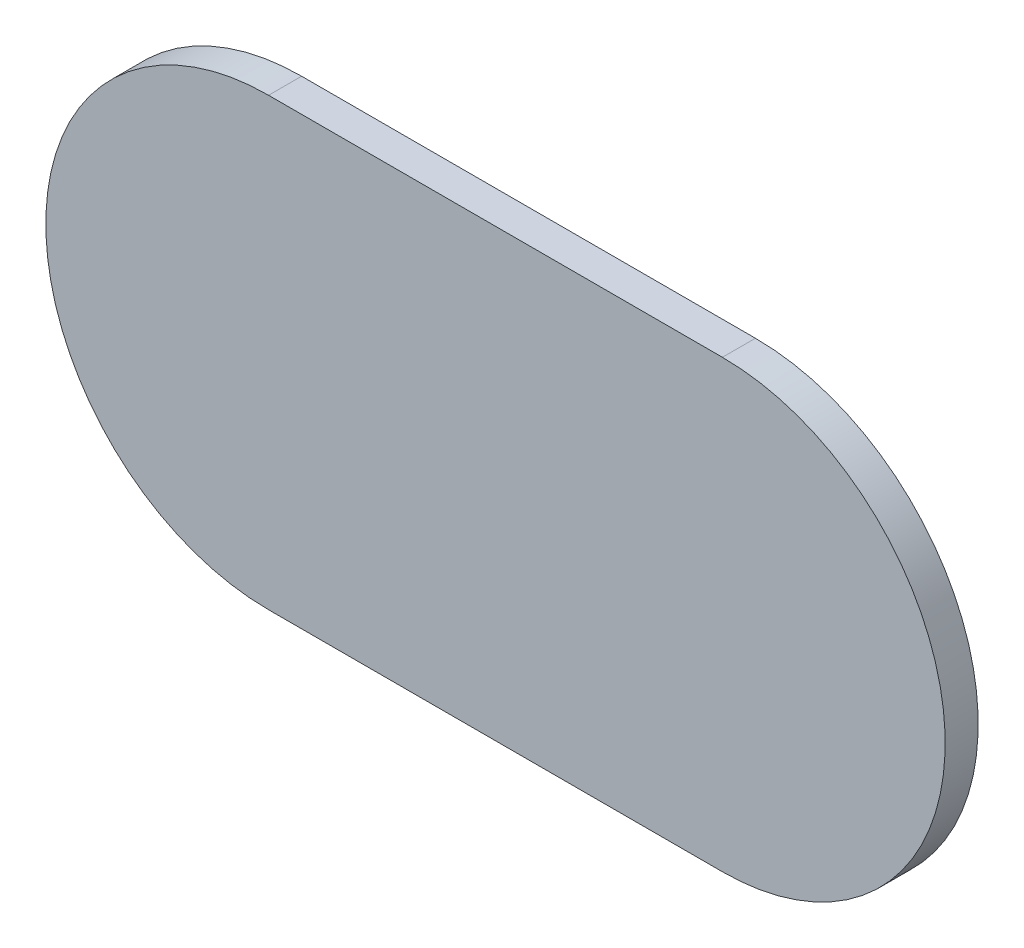
SolidWorks part; units mm, degrees
material "Acrylique (impact moyen-haut)"
ref_plane "Plan de face" through (0, 0, 0) normal (0, 0, 1) x (1, 0, 0)
ref_plane "Plan de dessus" through (0, 0, 0) normal (0, 1, 0) x (1, 0, 0)
ref_plane "Plan de droite" through (0, 0, 0) normal (1, 0, 0) x (0, 0, -1)
sketch "Esquisse1" plane through (0, 0, 0) normal (0, 0, 1) x (1, 0, 0)
  line L0 (2.75, 0) -> (-2.75, 0) construction
  line L1 (2.75, -2.7) -> (-2.75, -2.7)
  line L2 (2.75, 2.7) -> (-2.75, 2.7)
  arc A1 (2.75, -2.7) -> (2.75, 2.7) centre (2.75, 0) ccw
  arc A2 (-2.75, 2.7) -> (-2.75, -2.7) centre (-2.75, 0) ccw
  point P3 (0, 0)
  dimension "D1" = 5.4
  dimension "D2" = 5.5
extrude "Boss.-Extru.1" add sketch "Esquisse1" along normal blind 0.4
